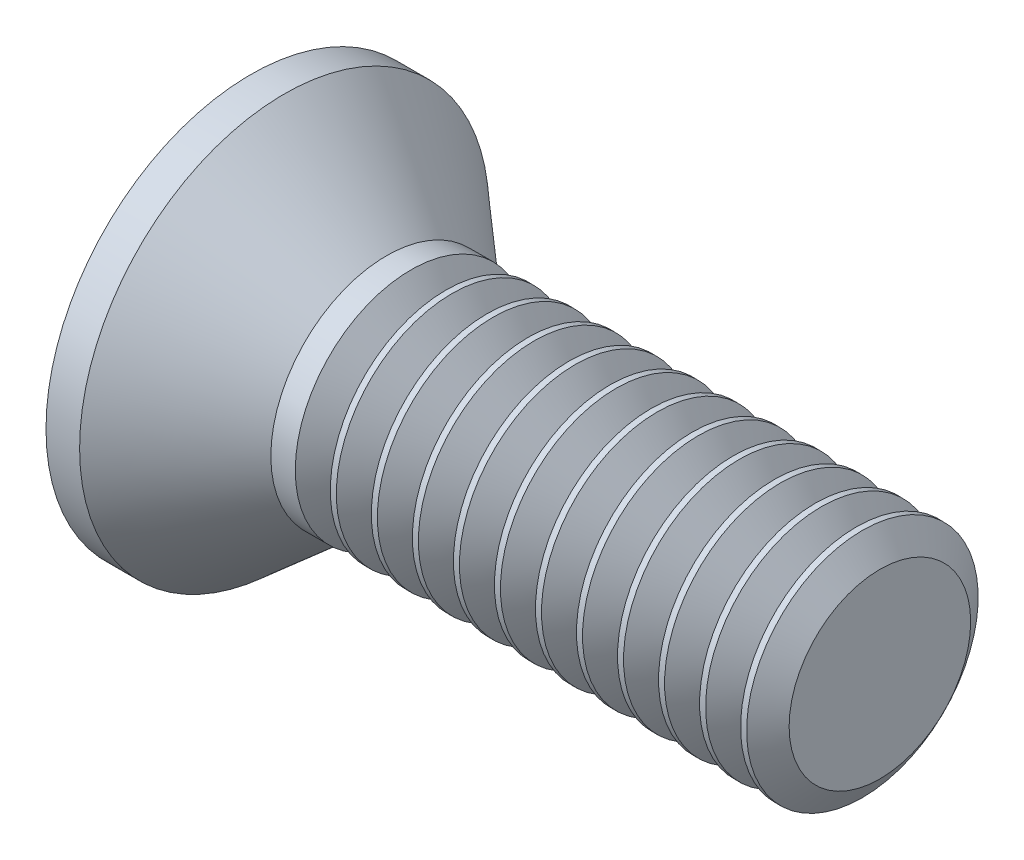
SolidWorks part; units mm, degrees
ref_plane "Plane1" through (0, 0, 0) normal (0, 0, 1) x (1, 0, 0)
ref_plane "Plane2" through (0, 0, 0) normal (0, 1, 0) x (1, 0, 0)
ref_plane "Plane3" through (0, 0, 0) normal (1, 0, 0) x (0, 0, -1)
sketch "BodySke" plane through (0, 0, 0) normal (0, 0, 1) x (1, 0, 0)
  line L0 (0, 0) -> (0, 3.0988)
  line L1 (0, 3.0988) -> (0.5088, 3.0988)
  line L2 (2.0574, 1.7526) -> (9.525, 1.7526)
  line L3 (9.525, 1.7526) -> (9.525, 0)
  line L4 (9.525, 0) -> (0, 0)
  line L5 (-6.35, 0) -> (82.55, 0) construction
  line L6 (2.0574, -1.7526) -> (9.525, -1.7526) construction
  line L7 (0.5088, -3.0988) -> (2.0574, -1.7526) construction
  line L8 (0.5088, 3.0988) -> (2.0574, 1.7526)
  line L9 (0, -3.0988) -> (0.5088, -3.0988) construction
  line L10 (2.6924, 3.3401) -> (2.6924, -6.1849) construction
  line L11 (0, 6.35) -> (0, -3.175) construction
  dimension "Diameter" = 3.5052
  dimension "Length" = 9.525
  dimension "Head_ht" = 2.0574
  dimension "Head_dia" = 6.1976
  dimension "Head_ang" = 82
  dimension "D6" = 0.5088
  dimension "Advance" = 0.635
  dimension "Thread_nom" = 9.525
revolve "Base-Revolve" add sketch "BodySke" angle 360 about L5
cosmetic thread "ThreadCosmetic" [suppressed] parameters "Thread_length"=6.8326, "Thread_minor"=2.7483
sketch "Sketch2" plane through (0, 0, 0) normal (-1, 0, 0) x (0, 0, 1)
  line L0 (-3.0988, -0.6096) -> (3.0988, -0.6096)
  line L1 (-3.0988, -0.6096) -> (-3.0988, 0.6096)
  line L2 (3.0988, 0.6096) -> (-3.0988, 0.6096)
  line L3 (3.0988, 0.6096) -> (3.0988, -0.6096)
  dimension "D1" = 0.6096
  dimension "Slot_width" = 1.2192
  dimension "D2" = 6.1976
  dimension "D3" = 3.0988
extrude "Slot" [suppressed] cut sketch "Sketch2" against normal blind 0.9652
sketch "Sketch3" plane through (0, 0, 0) normal (-1, 0, 0) x (0, 0, 1)
  line L0 (-0.4826, 2.4765) -> (0.4826, 2.4765)
  line L1 (0.4826, 2.4765) -> (0.4826, -2.4765)
  line L2 (0.4826, -2.4765) -> (-0.4826, -2.4765)
  line L3 (-0.4826, -2.4765) -> (-0.4826, 2.4765)
  dimension "D1" = 2.4765
  dimension "Cross_dia" = 4.953
  dimension "D2" = 0.4826
  dimension "Cross_width" = 0.9652
ref_plane "Plane4" through (2.8702, 0, 0) normal (-1, 0, 0) x (0, 0, 1)
sketch "Sketch4" plane through (2.8702, 0, 0) normal (-1, 0, 0) x (0, 0, 1)
  line L0 (-0.2413, 0.2413) -> (0.2413, 0.2413)
  line L3 (0.2413, 0.2413) -> (0.2413, -0.2413)
  line L4 (0.2413, -0.2413) -> (-0.2413, -0.2413)
  line L5 (-0.2413, -0.2413) -> (-0.2413, 0.2413)
  dimension "D1" = 0.4826
  dimension "D2" = 0.4826
  dimension "D3" = 0.2413
  dimension "D4" = 0.2413
loft "Cross" cut profiles "Sketch3", "Sketch4"
pattern_circular "CirPattern1" count 2 every 90 about axis through (0, 0, 0) along (1, 0, 0) of "Cross"
sketch "ThdSchSke" plane through (0, 0, 0) normal (0, 0, 1) x (1, 0, 0)
  line L0 (2.6924, -1.3741) -> (2.4274, -1.7526)
  line L1 (2.6924, -1.3741) -> (2.9574, -1.7526)
  line L2 (2.9574, -1.7526) -> (2.9574, -2.1907)
  line L3 (-3.175, 0) -> (5.1513, 0) construction
  line L5 (2.9574, -2.1907) -> (2.4274, -2.1907)
  line L6 (2.4274, -2.1907) -> (2.4274, -1.7526)
  line L7 (0, 3.0988) -> (0, -3.0988) construction
  dimension "Thread_minor" = 2.7483
  dimension "Diameter" = 3.5052
  dimension "Start" = 2.6924
  dimension "SideAngle" = 55
  dimension "VeeAngle" = 70
  dimension "Overcut" = 4.3815
revolve "ThreadSchematic" cut sketch "ThdSchSke" angle 360 about L3
pattern_linear "ThdSchPat" count 12 spacing 0.6211 along (1, 0, 0) of "ThreadSchematic"
equation "\"D1@Sketch3\" = \"Cross_dia@Sketch3\" / 2"
equation "\"D2@Sketch3\" = \"Cross_width@Sketch3\" / 2"
equation "\"D1@Sketch4\" = \"Cross_width@Sketch3\" *.5"
equation "\"D2@Sketch4\" = \"D1@Sketch4\""
equation "\"D4@Sketch4\" = \"D2@Sketch4\" / 2"
equation "\"D3@Sketch4\" = \"D1@Sketch4\" / 2"
equation "\"D1@Sketch2\" = \"Slot_width@Sketch2\" / 2"
equation "\"D2@Sketch2\" = \"Head_dia@BodySke\""
equation "\"D3@Sketch2\" = \"D2@Sketch2\" / 2"
equation "\"Thread_length@ThreadCosmetic\" = ((sgn( (\"Length@BodySke\" - \"Advance@BodySke\" - \"Head_ht@BodySke\" ) - \"Thread_nom@BodySke\" )-1)*( (\"Length@BodySke\" - \"Advance@BodySke\" - \"Head_ht@BodySke\" ) - \"Thread_nom@BodySke\" ))/-2+ \"Thread_nom@BodySke\""
equation "\"Thread_minor@ThdSchSke\" = \"Thread_minor@ThreadCosmetic\""
equation "\"Diameter@ThdSchSke\" = \"Diameter@BodySke\""
equation "\"Overcut@ThdSchSke\" = \"Diameter@BodySke\" * 1.25"
equation "\"Start@ThdSchSke\" = 0.000001 + \"Length@BodySke\" - \"Thread_length@ThreadCosmetic\"  '---Countersunk---"
equation "\"Num_threads@ThdSchPat\" = int( \"Thread_length@ThreadCosmetic\" / \"Advance@BodySke\" + 0.999 )  + 1"
equation "\"Advance@ThdSchPat\" = \"Thread_length@ThreadCosmetic\" /  (\"Num_threads@ThdSchPat\" - 1) 'relax it"
